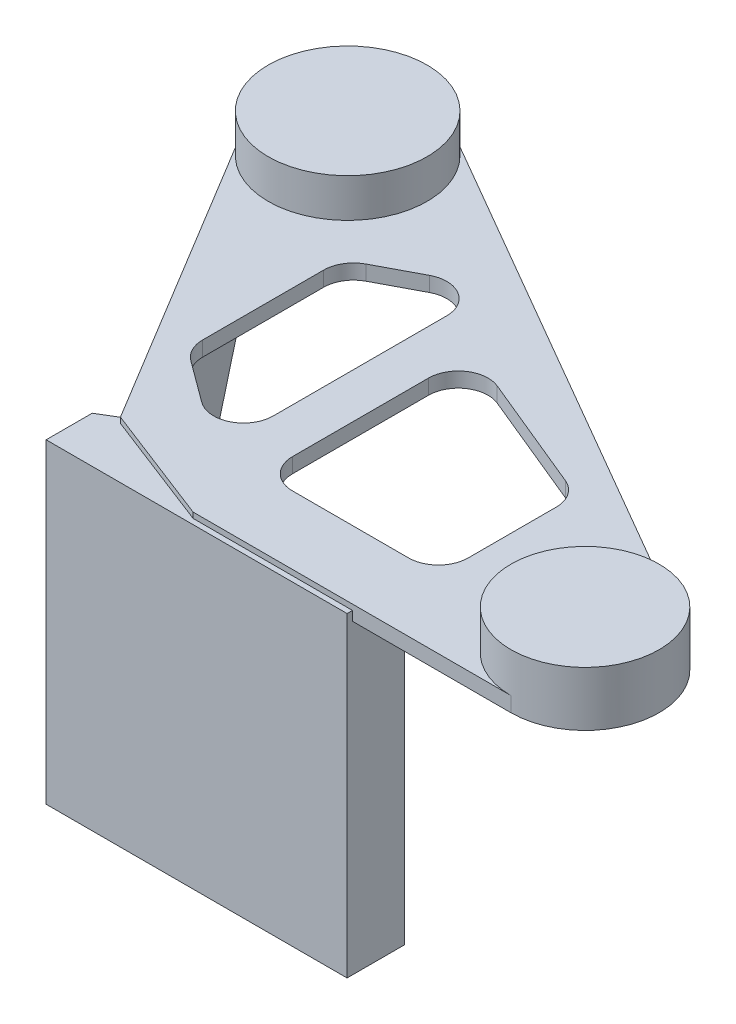
SolidWorks part; units mm, degrees
ref_plane "Front Plane" through (0, 0, 0) normal (0, 0, 1) x (1, 0, 0)
ref_plane "Top Plane" through (0, 0, 0) normal (0, 1, 0) x (1, 0, 0)
ref_plane "Right Plane" through (0, 0, 0) normal (1, 0, 0) x (0, 0, -1)
sketch "Sketch2" plane through (0, 0, 0) normal (0, 1, 0) x (1, 0, 0)
  line L0 (-394.1676, 144.5581) -> (-218.1839, -146.3538)
  line L1 (-218.1839, -146.3538) -> (-98.8152, -192.5611)
  line L2 (-98.8152, -192.5611) -> (221.1848, -192.5611)
  line L4 (-291.7486, 265.3131) -> (258.5787, -53.3636)
  line L5 (-394.1676, 144.5581) -> (-399.0062, 152.627)
  arc A0 (-291.7486, 265.3131) -> (-399.0062, 152.627) centre (-331.8377, 196.0826) ccw
  arc A1 (221.1848, -192.5611) -> (258.5787, -53.3636) centre (221.1848, -117.9396) ccw
  dimension "D1" = 340
  dimension "D7" = 160
  dimension "D2" = 128
  dimension "D3" = 320
extrude "Boss-Extrude1" add sketch "Sketch2" along normal blind 15
sketch "Sketch3" plane through (-224.5462, 0, 135.8366) normal (-0.8556, 0, 0.5176) x (0.5176, 0, 0.8556)
  line L0 (-327.7081, 0) -> (-327.7081, -65)
  line L1 (-327.7081, -65) -> (-7.7081, -308.3187)
  line L2 (-7.7081, -308.3187) -> (12.2919, -308.3187)
  line L3 (12.2919, -308.3187) -> (12.2919, 0)
  line L4 (12.2919, 0) -> (-327.7081, 0)
  dimension "D1" = 65
  dimension "D2" = 402
  dimension "D3" = 20
extrude "Boss-Extrude4" add sketch "Sketch3" against normal blind 15
sketch "Sketch4" plane through (0, 15, 0) normal (0, 1, 0) x (1, 0, 0)
  circle A0 centre (221.1848, -117.9396) radius 74.6215
extrude "Boss-Extrude5" add sketch "Sketch4" along normal blind 40
sketch "Sketch5" plane through (0, 15, 0) normal (0, 1, 0) x (1, 0, 0)
  circle A0 centre (-331.8377, 196.0826) radius 80
extrude "Boss-Extrude6" add sketch "Sketch5" along normal blind 39 and the other way blind 30
ref_plane "Plane1" through (0, 0, 140) normal (0, 0, 1) x (1, 0, 0)
sketch "Sketch6" plane through (0, 0, 140) normal (0, 0, 1) x (1, 0, 0)
  line L0 (-223.3599, 9.4661) -> (61.6401, 9.4661)
  line L1 (61.6401, 9.4661) -> (61.6401, -308.3187)
  line L2 (61.6401, -308.3187) -> (-223.3599, -308.3187)
  line L3 (-223.3599, -308.3187) -> (-223.3599, 9.4661)
  line L4 (-228.5359, -308.3187) -> (-218.1839, -308.3187) construction
  dimension "D1" = 285
extrude "Boss-Extrude7" add sketch "Sketch6" along normal blind 58 separate body
sketch "Sketch7" plane through (-223.3599, 0, 0) normal (-1, 0, 0) x (0, 0, 1)
  line L0 (140, -308.3187) -> (198, -308.3187)
  line L1 (198, -308.3187) -> (198, 9.4661)
  line L2 (198, 9.4661) -> (140, 9.4661)
  line L3 (140, 9.4661) -> (140, -308.3187)
extrude "Boss-Extrude8" add sketch "Sketch7" along normal blind 18
sketch "Sketch9" plane through (-224.5462, 0, 135.8366) normal (-0.8556, 0, 0.5176) x (0.5176, 0, 0.8556)
  line L7 (4.8659, 9.4661) -> (12.2919, 9.4661)
  line L9 (12.2919, 9.4661) -> (12.2919, 15)
  line L10 (12.2919, 15) -> (-327.7081, 15)
  line L11 (-327.7081, 15) -> (-327.7081, 0)
  line L12 (-327.7081, 0) -> (-327.7081, -65)
  line L13 (-327.7081, -65) -> (-7.7081, -308.3187)
  line L14 (-7.7081, -308.3187) -> (4.8659, -308.3187)
  line L17 (12.2919, 9.4661) -> (12.2919, 15)
  line L18 (12.2919, 15) -> (-327.7081, 15)
  line L19 (-327.7081, 15) -> (-327.7081, 0)
  line L20 (-327.7081, 0) -> (-327.7081, -65)
  line L21 (-327.7081, -65) -> (-7.7081, -308.3187)
  line L22 (-7.7081, -308.3187) -> (4.8659, -308.3187)
  line L24 (4.8659, 9.4661) -> (12.2919, 9.4661)
  line L25 (4.8659, -308.3187) -> (4.8659, 9.4661)
  line L26 (4.8659, -308.3187) -> (4.8659, 9.4661)
  dimension "D1" = 0
extrude "Cut-Extrude1" cut sketch "Sketch9" along normal blind 38
sketch "Sketch10" plane through (0, 15, 0) normal (0, 1, 0) x (1, 0, 0)
  line L0 (-97.1479, 42.7744) -> (-97.1479, -94.0851)
  line L1 (-67.1479, -124.0851) -> (49.6669, -124.0851)
  line L2 (79.6669, -94.0851) -> (79.6669, -5.4259)
  line L3 (61.1097, 22.3061) -> (-55.7051, 70.5063)
  arc A0 (49.6669, -124.0851) -> (79.6669, -94.0851) centre (49.6669, -94.0851) ccw
  arc A1 (-97.1479, -94.0851) -> (-67.1479, -124.0851) centre (-67.1479, -94.0851) ccw
  arc A2 (79.6669, -5.4259) -> (61.1097, 22.3061) centre (49.6669, -5.4259) ccw
  arc A3 (-97.1479, 42.7744) -> (-55.7051, 70.5063) centre (-67.1479, 42.7744) cw
  dimension "D1" = 30
extrude "Cut-Extrude2" cut sketch "Sketch10" against normal blind 40
sketch "Sketch11" plane through (0, 15, 0) normal (0, 1, 0) x (1, 0, 0)
  line L0 (-244.0992, 84.1932) -> (-244.0992, -37.6252)
  line L1 (-231.8789, -61.7889) -> (-190.0411, -92.5732)
  line L2 (-142.2614, -68.4095) -> (-142.2614, 106.2764)
  line L3 (-186.2653, 132.8074) -> (-228.103, 110.7242)
  arc A0 (-244.0992, -37.6252) -> (-231.8789, -61.7889) centre (-214.0992, -37.6252) ccw
  arc A1 (-190.0411, -92.5732) -> (-142.2614, -68.4095) centre (-172.2614, -68.4095) ccw
  arc A2 (-142.2614, 106.2764) -> (-186.2653, 132.8074) centre (-172.2614, 106.2764) ccw
  arc A3 (-244.0992, 84.1932) -> (-228.103, 110.7242) centre (-214.0992, 84.1932) cw
  dimension "D1" = 30
extrude "Cut-Extrude3" cut sketch "Sketch11" against normal blind 40
